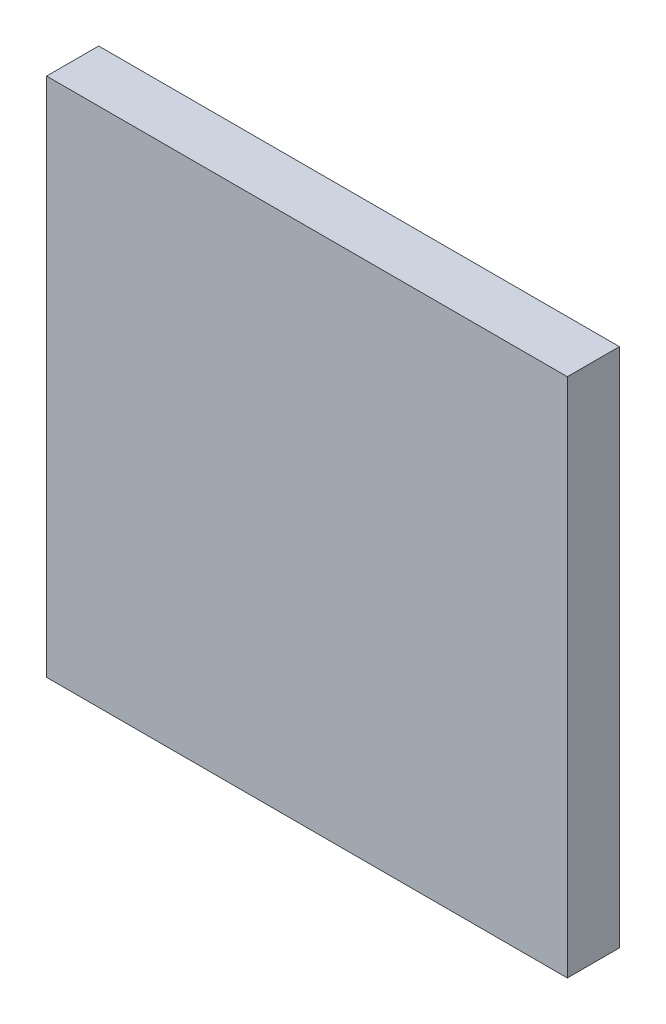
SolidWorks part; units mm, degrees
ref_plane "Front Plane" through (0, 0, 0) normal (0, 0, 1) x (1, 0, 0)
ref_plane "Top Plane" through (0, 0, 0) normal (0, 1, 0) x (1, 0, 0)
ref_plane "Right Plane" through (0, 0, 0) normal (1, 0, 0) x (0, 0, -1)
sketch "Sketch1" plane through (0, 0, 0) normal (0, 0, 1) x (1, 0, 0)
  line L1 (0, 0) -> (1000, 0)
  line L2 (0, 0) -> (0, 1000)
  line L3 (0, 1000) -> (1000, 1000)
  line L4 (1000, 0) -> (1000, 1000)
  dimension "D1" = 1000
  dimension "D2" = 1000
extrude "Boss-Extrude1" add sketch "Sketch1" along normal blind 100
sketch "Sketch2" plane through (0, 0, 0) normal (0, -1, 0) x (1, 0, 0)
  line L1 (0, 100) -> (1000, 100) construction
  line L2 (0, 0) -> (1000, 0) construction
  line L3 (450, 100) -> (450, 0)
  line L4 (550, 100) -> (550, 0)
  line L6 (0, 100) -> (0, 0) construction
  dimension "D3" = 100
  dimension "D4" = 450
split line "Split Line1"
